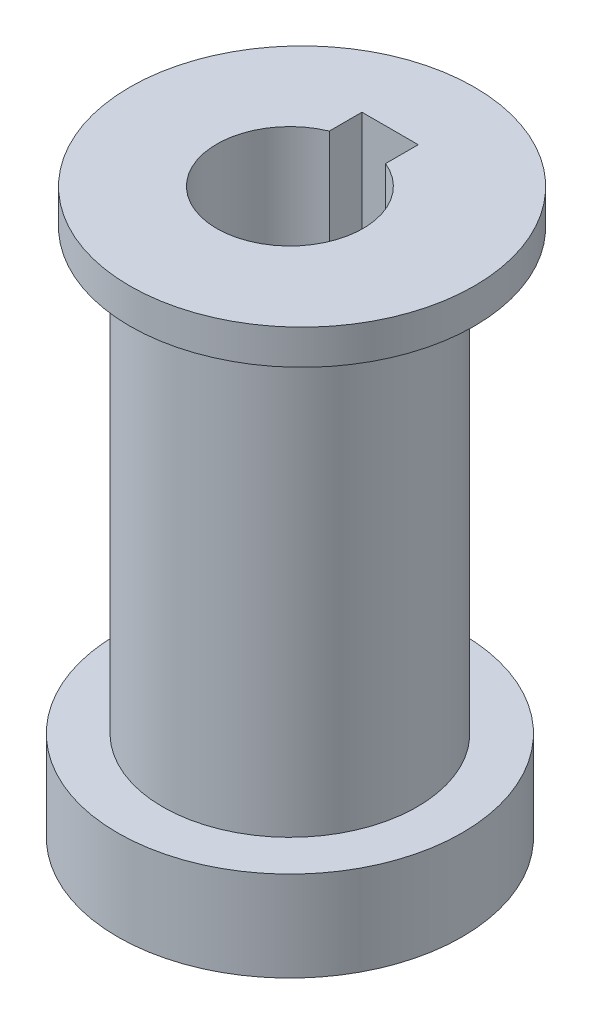
SolidWorks part; units mm, degrees
material "6061 Alloy"
ref_plane "Front Plane" through (0, 0, 0) normal (0, 0, 1) x (1, 0, 0)
ref_plane "Top Plane" through (0, 0, 0) normal (0, 1, 0) x (1, 0, 0)
ref_plane "Right Plane" through (0, 0, 0) normal (1, 0, 0) x (0, 0, -1)
sketch "Sketch1" plane through (0, 0, 0) normal (0, 1, 0) x (1, 0, 0)
  circle A0 centre (0, 0) radius 15.3
extrude "Boss-Extrude1" add sketch "Sketch1" along normal blind 8
sketch "Sketch2" plane through (0, 8, 0) normal (0, 1, 0) x (1, 0, 0)
  circle A0 centre (0, 0) radius 11.3
extrude "Boss-Extrude2" add sketch "Sketch2" along normal blind 39
sketch "Sketch3" plane through (0, 47, 0) normal (0, 1, 0) x (1, 0, 0)
  circle A0 centre (0.5592, 0.5242) radius 15.3
extrude "Boss-Extrude3" add sketch "Sketch3" along normal blind 3.0887
sketch "Sketch6" plane through (0, 50.0887, 0) normal (0, 1, 0) x (1, 0, 0)
  line L1 (-2.5, 8.9) -> (2.5, 8.9)
  line L2 (-2.5, 8.9) -> (-2.5, 6)
  line L3 (2.5, 8.9) -> (2.5, 6)
  arc A0 (-2.5, 6) -> (2.5, 6) centre (0, 0) ccw
  point P8 (0, 8.9)
extrude "Cut-Extrude4" cut sketch "Sketch6" against normal blind 51
